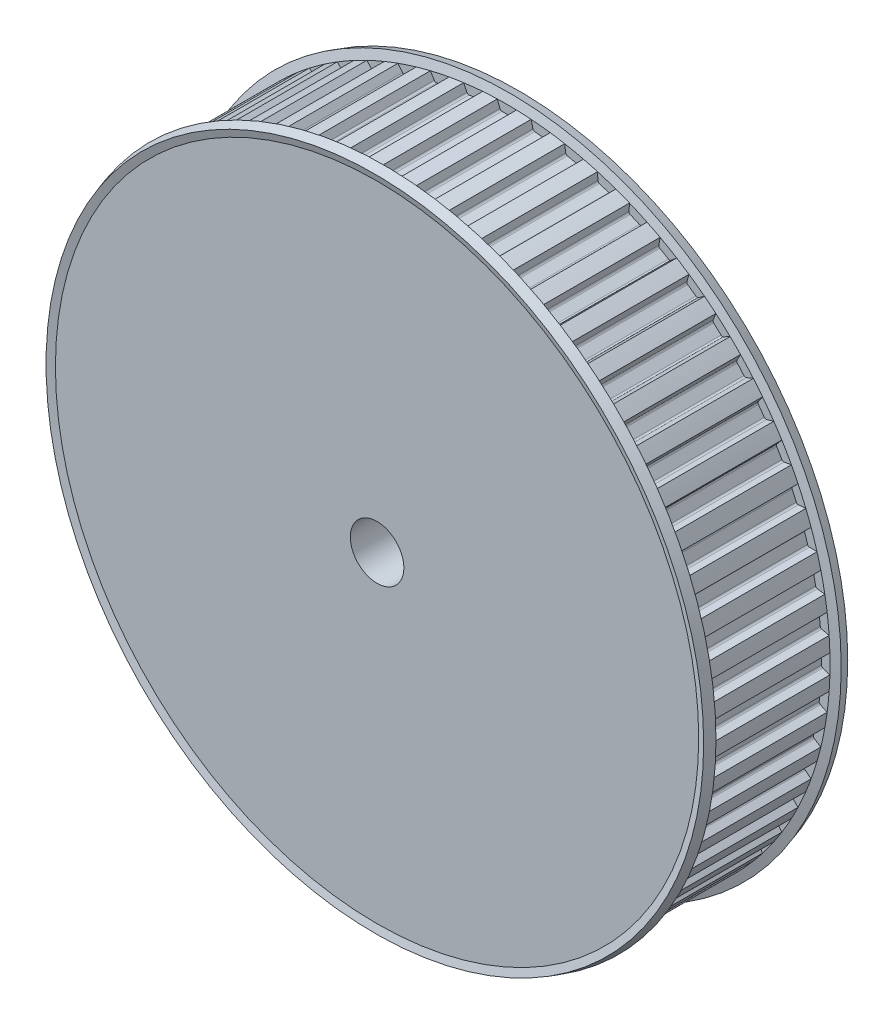
SolidWorks part; units mm, degrees
extrude "BasePulley" add sketch "Sketch1" against normal blind 7.112
sketch "Sketch1" plane through (0, 0, 0) normal (0, 0, 1) x (1, 0, 0)
  circle A0 centre (0, 0) radius 19.1516
  dimension "Outside_dia" = 38.3032
revolve "Flange" add sketch "Sketch2" angle 360 about L11
sketch "Sketch2" plane through (0, 0, 0) normal (1, 0, 0) x (0, 0, -1)
  line L0 (7.112, 19.1516) -> (7.2673, 19.6596)
  line L1 (7.2673, 19.6596) -> (7.826, 19.4888)
  line L2 (3.556, 0) -> (3.556, 66.675) construction
  line L3 (7.826, 19.4888) -> (7.6962, 19.0643)
  line L4 (7.6962, 19.0643) -> (7.6962, 0)
  line L5 (0, 19.1516) -> (-0.1553, 19.6596)
  line L6 (7.112, -19.1516) -> (7.112, 19.1516) construction
  line L7 (-0.1553, 19.6596) -> (-0.714, 19.4888)
  line L8 (-0.714, 19.4888) -> (-0.5842, 19.0643)
  line L9 (-0.5842, 19.0643) -> (-0.5842, 0)
  line L10 (7.112, 19.1516) -> (0, 19.1516)
  line L11 (0, 0) -> (38.2092, 0) construction
  line L12 (7.112, 0) -> (0, 0) construction
  line L13 (-0.5842, 0) -> (7.6962, 0)
  dimension "D1" = 3.556
  dimension "Flange_ang" = 17
  dimension "D3" = 0.5842
  dimension "D2" = 19.1516
  dimension "Flange_ht" = 0.508
ref_plane "Plane1" through (0, 0, 0) normal (0, 0, 1) x (1, 0, 0)
ref_plane "Plane2" through (0, 0, 0) normal (0, 1, 0) x (1, 0, 0)
ref_plane "Plane3" through (0, 0, 0) normal (1, 0, 0) x (0, 0, -1)
sketch "Clipboard" plane through (0, 0, 0) normal (0, 0, 1) x (1, 0, 0)
  line L0 (0, 0) -> (3.429, 0)
  line L1 (0, 0) -> (7.62, 13.1982)
  line L2 (0, 0) -> (7.62, -13.1982)
ref_plane "Plane4" through (0, 0, -3.556) normal (0, 0, 1) x (1, 0, 0)
sketch "Sketch3" plane through (0, 0, -3.556) normal (0, 0, 1) x (1, 0, 0)
  line L0 (-0.5715, 19.1516) -> (-0.5715, 44.5516)
  line L1 (0.5715, 19.1516) -> (0.5715, 44.5516)
  line L2 (0, 0) -> (0, 19.1516) construction
  line L3 (-0.5715, 19.1516) -> (0.5715, 19.1516) construction
  line L4 (-0.2977, 18.6436) -> (0.2977, 18.6436)
  line L5 (0.5715, 19.1516) -> (0.417, 18.7272)
  line L6 (-0.5715, 19.1516) -> (-0.417, 18.7272)
  line L7 (0.5715, 44.5516) -> (-0.5715, 44.5516)
  arc A0 (0.2977, 18.6436) -> (0.417, 18.7272) centre (0.2977, 18.7706) ccw
  arc A2 (-0.417, 18.7272) -> (-0.2977, 18.6436) centre (-0.2977, 18.7706) ccw
  dimension "Grv_rad_bot" = 0.127
  dimension "Grv_ang" = 40
  dimension "D3" = 20
  dimension "Grv_width" = 1.143
  dimension "D4" = 25.4
  dimension "D1" = 19.1516
  dimension "Grv_depth" = 0.508
extrude "Groove" cut sketch "Sketch3" against normal mid plane 7.112
pattern_circular "Grooves" count 60 every 6 about axis through (0, 0, -7.112) along (0, 0, 1) of "Groove"
sketch "Sketch4" plane through (0, 0, 0) normal (1, 0, 0) x (0, 0, -1)
  line L0 (0, 0) -> (47.6781, 0) construction
  line L1 (7.112, 0) -> (0, 0) construction
  line L2 (0, 0) -> (8.128, 0)
  line L3 (8.128, 0) -> (8.128, 6.35)
  line L4 (8.128, 6.35) -> (0, 6.35)
  line L5 (0, 6.35) -> (0, 0)
  line L6 (8.128, -6.35) -> (0, -6.35) construction
revolve "BaseHub" add sketch "Sketch4" angle 360 about L0
sketch "BorSke" plane through (0, 0, -8.128) normal (0, 0, -1) x (-1, 0, 0)
  circle A0 centre (0, 0) radius 1.5875
extrude "Bore" cut sketch "BorSke" against normal through all
sketch "KeySke" plane through (0, 0, -8.128) normal (0, 0, -1) x (-1, 0, 0)
  line L0 (0.127, 1.8415) -> (0.127, 0)
  line L1 (0.127, 1.8415) -> (-0.127, 1.8415)
  line L2 (-0.127, 1.8415) -> (-0.127, 0)
  line L3 (-0.127, 0) -> (0.127, 0)
  line L4 (0, 31.75) -> (0, -3.175) construction
  dimension "Width" = 7.112
extrude "Keyway" [suppressed] cut sketch "KeySke" against normal through all
pattern_circular "Keyway2" [suppressed] count 2 every 90
equation "\"D1@Plane4\" = \"Width@BasePulley\" / 2"
equation "\"D1@Groove\" = \"Width@BasePulley\""
equation "\"D1@Sketch3\" = \"Outside_dia@Sketch1\" / 2"
equation "\"D1@Sketch2\" = \"Width@BasePulley\" / 2"
equation "\"D2@Sketch2\" = \"Outside_dia@Sketch1\" / 2"
equation "\"D3@Sketch2\" = \"Flange_thickness@Sketch2\""
equation "\"Num_grvs@Clipboard\" = int( \"Num_grvs@Clipboard\" )"
equation "\"Show_grvs@Clipboard\" = int( \"Show_grvs@Clipboard\" )"
equation "\"Show_grvs@Clipboard\" = ((sgn( \"Show_grvs@Clipboard\" - \"Num_grvs@Clipboard\" )-1)*( \"Show_grvs@Clipboard\" - \"Num_grvs@Clipboard\" ))/-2+ \"Num_grvs@Clipboard\""
equation "\"Show_grvs@Clipboard\" = ((sgn( \"Show_grvs@Clipboard\" - 1.0)+1)*( \"Show_grvs@Clipboard\" - 1.0))/2 +1.0"
equation "\"Angle@Grooves\" = 360.0 / \"Num_grvs@Clipboard\""
equation "\"Num_grvs@Grooves\" =  \"Show_grvs@Clipboard\""
equation "\"Offset@KeySke\" = \"T_dim@Clipboard\" - \"Diameter@BorSke\" / 2.0"
equation "\"OAL@Clipboard\" = \"Overall_len@Clipboard\""
equation "\"Hub_depth@Sketch4\" = \"OAL@Clipboard\" - \"Width@BasePulley\""
